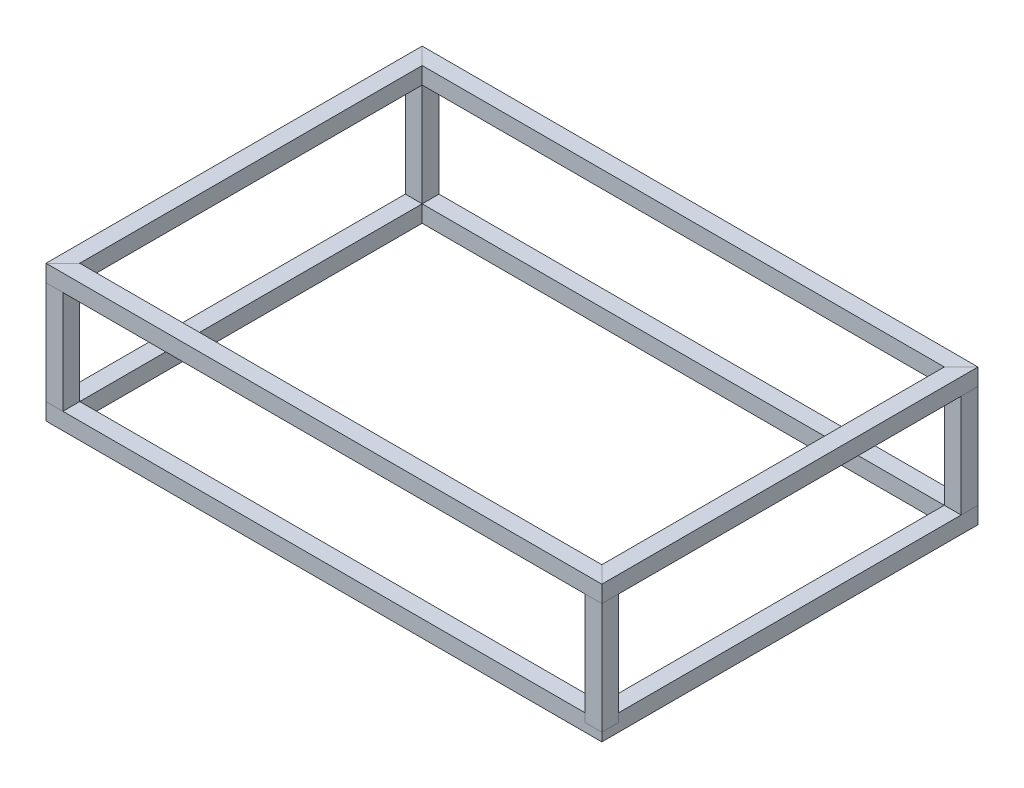
SolidWorks part; units mm, degrees
ref_plane "Front Plane" through (0, 0, 0) normal (0, 0, 1) x (1, 0, 0)
ref_plane "Top Plane" through (0, 0, 0) normal (0, 1, 0) x (1, 0, 0)
ref_plane "Right Plane" through (0, 0, 0) normal (1, 0, 0) x (0, 0, -1)
sketch "Sketch1" plane through (0, 0, 0) normal (0, 1, 0) x (1, 0, 0)
  line L1 (-457.2, 304.8) -> (457.2, 304.8)
  line L2 (-457.2, 304.8) -> (-457.2, -304.8)
  line L3 (-457.2, -304.8) -> (457.2, -304.8)
  line L4 (457.2, 304.8) -> (457.2, -304.8)
  line L5 (-457.2, 304.8) -> (457.2, -304.8) construction
  line L6 (-457.2, -304.8) -> (457.2, 304.8) construction
  point P0 (0, 0)
  dimension "D1" = 609.6
  dimension "D2" = 914.4
sketch3d "3DSketch2"
  line L0 (-457.2, 0, 304.8) -> (-457.2, 203.2, 304.8)
  line L1 (457.2, 0, 304.8) -> (457.2, 203.2, 304.8)
  line L2 (457.2, 0, -304.8) -> (457.2, 203.2, -304.8)
  line L3 (-457.2, 0, -304.8) -> (-457.2, 203.2, -304.8)
  dimension "D1" = 203.2
ref_plane "Plane1" through (0, 203.2, 0) normal (0, 1, 0) x (1, 0, 0)
sketch "Sketch2" plane through (0, 203.2, 0) normal (0, 1, 0) x (1, 0, 0)
  line L1 (-457.2, 304.8) -> (457.2, 304.8)
  line L2 (-457.2, 304.8) -> (-457.2, -304.8)
  line L3 (-457.2, -304.8) -> (457.2, -304.8)
  line L4 (457.2, 304.8) -> (457.2, -304.8)
other "Square tube 25.4X25.4X1.6_IGVC(1)"
ref_plane "Plane2" through (-457.2, 0, 304.8) normal (1, 0, 0) x (0, 0, -1)
sketch "Sketch14" plane through (-457.2, 0, 304.8) normal (1, 0, 0) x (0, 0, -1)
  line L0 (-14.3, 14.3) -> (-14.3, -14.3)
  line L1 (-12.7, 12.7) -> (12.7, 12.7)
  line L2 (-12.7, 12.7) -> (-12.7, -12.7)
  line L3 (-12.7, -12.7) -> (12.7, -12.7)
  line L4 (12.7, 12.7) -> (12.7, -12.7)
  line L7 (-14.3, -14.3) -> (14.3, -14.3)
  line L8 (14.3, 14.3) -> (14.3, -14.3)
  line L9 (-14.3, 14.3) -> (14.3, 14.3)
  point P0 (0, 0)
  point P10 (0, 0)
  dimension "D1" = 25.4
  dimension "D2" = 25.4
  dimension "D3" = 1.6
other "Square tube 25.4X25.4X1.6_IGVC(2)"
ref_plane "Plane3" through (-457.2, 0, 304.8) normal (0, 1, 0) x (1, 0, 0)
sketch "Sketch15" plane through (-457.2, 0, 304.8) normal (0, 1, 0) x (1, 0, 0)
  line L0 (-14.3, 14.3) -> (-14.3, -14.3)
  line L1 (-12.7, 12.7) -> (12.7, 12.7)
  line L2 (-12.7, 12.7) -> (-12.7, -12.7)
  line L3 (-12.7, -12.7) -> (12.7, -12.7)
  line L4 (12.7, 12.7) -> (12.7, -12.7)
  line L7 (-14.3, -14.3) -> (14.3, -14.3)
  line L8 (14.3, 14.3) -> (14.3, -14.3)
  line L9 (-14.3, 14.3) -> (14.3, 14.3)
  point P0 (0, 0)
  point P10 (0, 0)
  dimension "D1" = 25.4
  dimension "D2" = 25.4
  dimension "D3" = 1.6
other "Square tube 25.4X25.4X1.6_IGVC(3)"
ref_plane "Plane4" through (-457.2, 203.2, -304.8) normal (0, 0, 1) x (1, 0, 0)
sketch "Sketch16" plane through (-457.2, 203.2, -304.8) normal (0, 0, 1) x (1, 0, 0)
  line L0 (-14.3, 14.3) -> (-14.3, -14.3)
  line L1 (-12.7, 12.7) -> (12.7, 12.7)
  line L2 (-12.7, 12.7) -> (-12.7, -12.7)
  line L3 (-12.7, -12.7) -> (12.7, -12.7)
  line L4 (12.7, 12.7) -> (12.7, -12.7)
  line L7 (-14.3, -14.3) -> (14.3, -14.3)
  line L8 (14.3, 14.3) -> (14.3, -14.3)
  line L9 (-14.3, 14.3) -> (14.3, 14.3)
  point P0 (0, 0)
  point P10 (0, 0)
  dimension "D1" = 25.4
  dimension "D2" = 25.4
  dimension "D3" = 1.6
